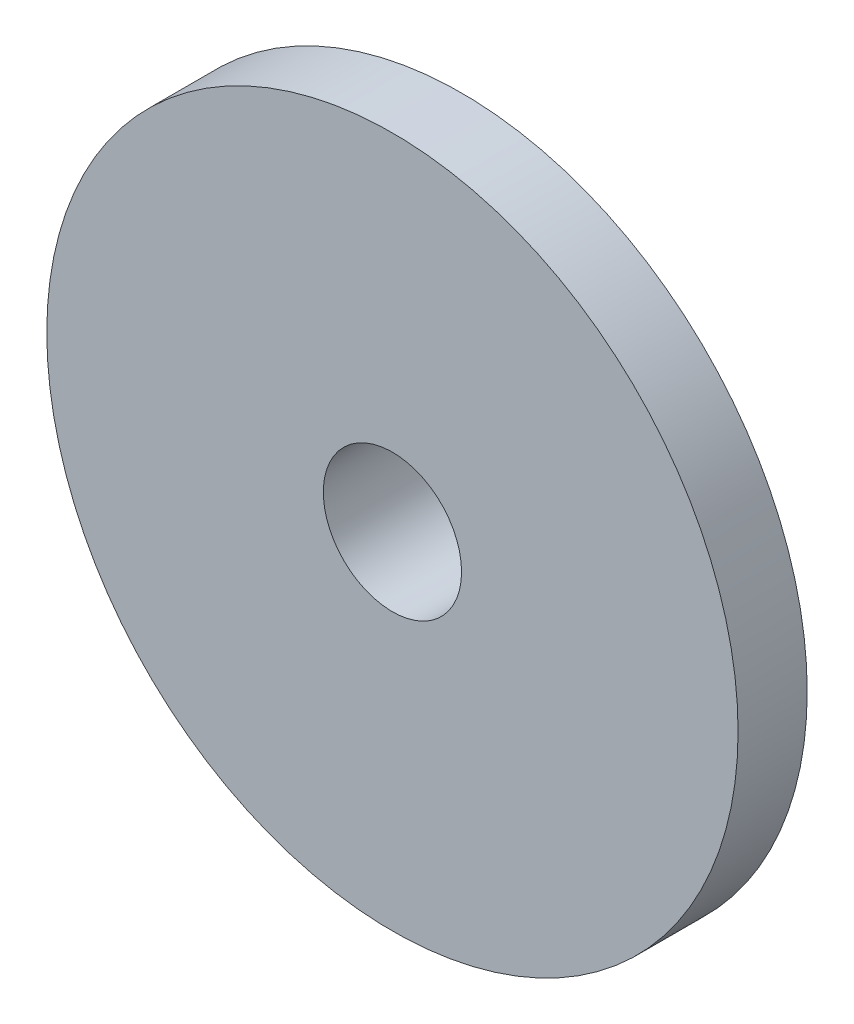
SolidWorks part; units mm, degrees
ref_plane "Front Plane" through (0, 0, 0) normal (0, 0, 1) x (1, 0, 0)
ref_plane "Top Plane" through (0, 0, 0) normal (0, 1, 0) x (1, 0, 0)
ref_plane "Right Plane" through (0, 0, 0) normal (1, 0, 0) x (0, 0, -1)
sketch "Sketch1" plane through (0, 0, 0) normal (0, 0, 1) x (1, 0, 0)
  circle A0 centre (0, 0) radius 1.5
  circle A1 centre (0, 0) radius 3.5
  dimension "D1" = 7
  dimension "D2" = 3
extrude "Boss-Extrude1" add sketch "Sketch1" along normal blind 1
sketch "Sketch2" plane through (0, 0, 1) normal (0, 0, 1) x (1, 0, 0)
  circle A0 centre (0, 0) radius 7.5
  circle A1 centre (0, 0) radius 1.5
  dimension "D1" = 15
extrude "Boss-Extrude2" add sketch "Sketch2" along normal blind 1.5
